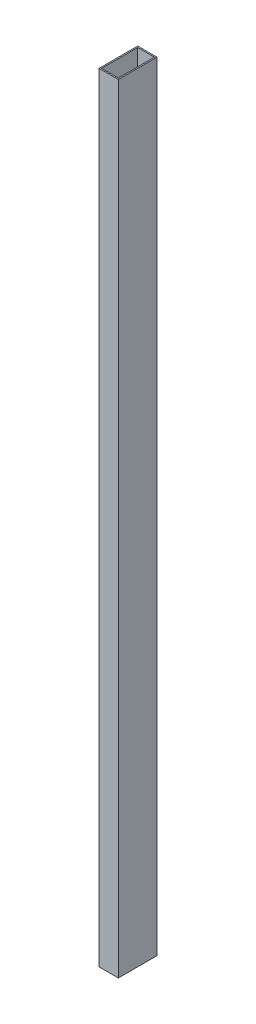
SolidWorks part; units mm, degrees
material "6061 Alloy"
ref_plane "Front Plane" through (0, 0, 0) normal (0, 0, 1) x (1, 0, 0)
ref_plane "Top Plane" through (0, 0, 0) normal (0, 1, 0) x (1, 0, 0)
ref_plane "Right Plane" through (0, 0, 0) normal (1, 0, 0) x (0, 0, -1)
sketch "Sketch1" plane through (0, 0, 0) normal (0, 1, 0) x (1, 0, 0)
  line L1 (-58.793, -42.5707) -> (-33.393, -42.5707)
  line L2 (-58.793, -42.5707) -> (-58.793, 8.2293)
  line L3 (-58.793, 8.2293) -> (-33.393, 8.2293)
  line L4 (-33.393, -42.5707) -> (-33.393, 8.2293)
  line L5 (-57.142, 6.5783) -> (-35.044, 6.5783)
  line L6 (-57.142, 6.5783) -> (-57.142, -40.9197)
  line L7 (-57.142, -40.9197) -> (-35.044, -40.9197)
  line L8 (-35.044, 6.5783) -> (-35.044, -40.9197)
  line L9 (-57.142, 6.5783) -> (-35.044, -40.9197) construction
  line L10 (-57.142, -40.9197) -> (-35.044, 6.5783) construction
  point P4 (-46.093, -17.1707)
  dimension "D1" = 25.4
  dimension "D2" = 50.8
  dimension "D3" = 1.651
  dimension "D4" = 1.651
  dimension "D5" = 1.651
  dimension "D6" = 1.651
extrude "Boss-Extrude1" add sketch "Sketch1" along normal blind 1022.35
